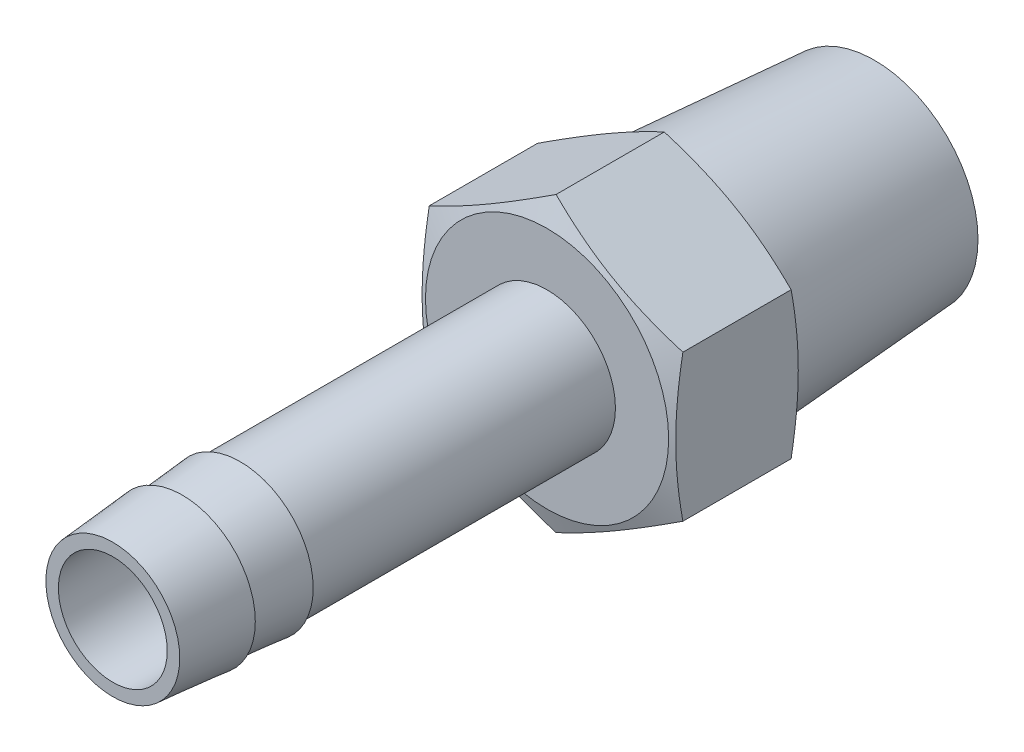
SolidWorks part; units mm, degrees
ref_plane "Front Plane" through (0, 0, 0) normal (0, 0, 1) x (1, 0, 0)
ref_plane "Top Plane" through (0, 0, 0) normal (0, 1, 0) x (1, 0, 0)
ref_plane "Right Plane" through (0, 0, 0) normal (1, 0, 0) x (0, 0, -1)
sketch "Sketch1" plane through (0, 0, 0) normal (1, 0, 0) x (0, 0, -1)
  line L0 (-4.1271, 2.3876) -> (-24.5911, 2.3876)
  line L1 (-24.5911, 2.3876) -> (-24.5911, 2.9365)
  line L2 (-24.5911, 2.9365) -> (-21.5431, 3.2032)
  line L7 (-18.9854, 3) -> (-5.5411, 3)
  line L8 (-5.5411, 3) -> (-5.5411, 5.334)
  line L9 (-5.5411, 5.334) -> (-4.6167, 7.874)
  line L10 (-4.6167, 7.874) -> (-0.9245, 7.874)
  line L11 (-0.9245, 7.874) -> (0, 5.334)
  line L12 (0, 5.334) -> (0, 5.1562)
  line L13 (0, 5.1562) -> (8.8255, 4.5391)
  line L14 (8.8255, 4.5391) -> (8.8255, 2.5781)
  line L15 (-4.1271, 2.3876) -> (-4.0171, 2.5781)
  line L16 (-4.0171, 2.5781) -> (8.8255, 2.5781)
  line L17 (2.002, 0) -> (9.2467, 0) construction
  line L18 (-21.5431, 3.2032) -> (-21.5239, 2.9827)
  line L19 (-21.5239, 2.9827) -> (-19.0031, 3.2032)
  line L20 (-19.0031, 3.2032) -> (-18.9854, 3)
  dimension "D2" = 5
  dimension "D3" = 6
  dimension "D4" = 3.048
  dimension "D5" = 20
  dimension "D6" = 20
  dimension "D7" = 19.05
  dimension "D8" = 0.2032
  dimension "D9" = 1.524
  dimension "D10" = 5.5411
  dimension "D11" = 8.8255
  dimension "D12" = 2.54
  dimension "D13" = 2.54
  dimension "D14" = 4.7752
  dimension "D15" = 5.1562
  dimension "D16" = 4
  dimension "D17" = 10.3124
  dimension "D18" = 10.668
  dimension "D19" = 60
revolve "Revolve1" add sketch "Sketch1" angle 360 about L17
sketch "Sketch2" plane through (0, 0, 0) normal (0, 0, 1) x (1, 0, 0)
  line L1 (0, 6.4231) -> (-5.5626, 3.2116)
  line L2 (-5.5626, 3.2116) -> (-5.5626, -3.2116)
  line L3 (-5.5626, -3.2116) -> (0, -6.4231)
  line L4 (0, -6.4231) -> (5.5626, -3.2116)
  line L5 (5.5626, -3.2116) -> (5.5626, 3.2116)
  line L6 (5.5626, 3.2116) -> (0, 6.4231)
  circle A0 centre (0, 0) radius 5.5626 construction
  dimension "D1" = 11.1252
extrude "Cut-Extrude1" cut sketch "Sketch2" along normal through all flip side to cut
